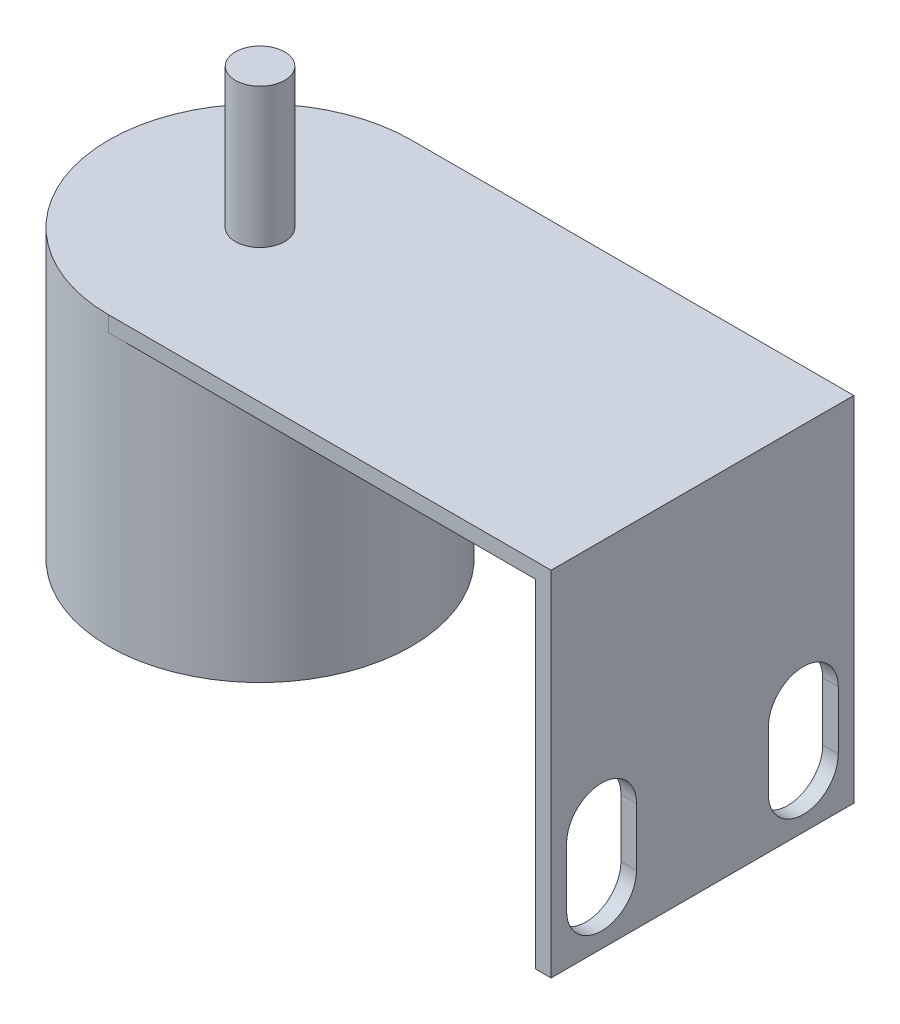
SolidWorks part; units mm, degrees
ref_plane "Plan de face" through (0, 0, 0) normal (0, 0, 1) x (1, 0, 0)
ref_plane "Plan de dessus" through (0, 0, 0) normal (0, 1, 0) x (1, 0, 0)
ref_plane "Plan de droite" through (0, 0, 0) normal (1, 0, 0) x (0, 0, -1)
sketch "Esquisse1" plane through (0, 0, 0) normal (0, 1, 0) x (1, 0, 0)
  circle A0 centre (0, 0) radius 19.5
  dimension "D1" = 39
extrude "Boss.-Extru.1" add sketch "Esquisse1" along normal blind 35
sketch "Esquisse2" plane through (0, 35, 0) normal (0, 1, 0) x (1, 0, 0)
  circle A0 centre (0, 0) radius 3.175
  dimension "D1" = 6.35
extrude "Boss.-Extru.2" add sketch "Esquisse2" along normal blind 20
sketch "Esquisse4" plane through (0, 35, 0) normal (0, 1, 0) x (1, 0, 0)
  line L1 (0, 19.5) -> (57, 19.5)
  line L3 (0, -19.5) -> (57, -19.5)
  line L4 (57, 19.5) -> (57, -19.5)
  circle A0 centre (0, 0) radius 19.5 construction
  arc A1 (0, 19.5) -> (0, -19.5) centre (0, 0) ccw
  point P7 (-19.5, 0)
  dimension "D1" = 76.5
extrude "Boss.-Extru.3" add sketch "Esquisse4" along normal blind 2
sketch "Esquisse5" plane through (0, 35, 0) normal (0, -1, 0) x (1, 0, 0)
  line L0 (57, -19.5) -> (0, -19.5) construction
  line L1 (57, 19.5) -> (55, 19.5)
  line L2 (57, 19.5) -> (57, -19.5)
  line L3 (57, -19.5) -> (55, -19.5)
  line L4 (55, 19.5) -> (55, -19.5)
  dimension "D1" = 2
extrude "Boss.-Extru.4" add sketch "Esquisse5" along normal blind 43.5
sketch "Esquisse6" plane through (57, 0, 0) normal (1, 0, 0) x (0, 0, -1)
  line L0 (-13, 5.5) -> (-13, -2) construction
  line L1 (-8.5, 5.5) -> (-8.5, -2)
  line L2 (-17.5, 5.5) -> (-17.5, -2)
  line L3 (0, 23.3853) -> (0, -17.6361) construction
  line L4 (-19.5, 37) -> (-19.5, -8.5) construction
  line L5 (19.5, -8.5) -> (-19.5, -8.5) construction
  line L6 (13, 5.5) -> (13, -2) construction
  line L7 (8.5, 5.5) -> (8.5, -2)
  line L8 (17.5, 5.5) -> (17.5, -2)
  arc A0 (-8.5, 5.5) -> (-17.5, 5.5) centre (-13, 5.5) ccw
  arc A1 (-17.5, -2) -> (-8.5, -2) centre (-13, -2) ccw
  arc A2 (8.5, 5.5) -> (17.5, 5.5) centre (13, 5.5) cw
  arc A3 (17.5, -2) -> (8.5, -2) centre (13, -2) cw
  point P2 (-13, 1.75)
  point P10 (-13, 10)
  point P11 (-13, -6.5)
  point P12 (-10.9885, -3.4761)
  point P19 (13, 1.75)
  dimension "D1" = 16.5
  dimension "D2" = 9
  dimension "D3" = 2
  dimension "D4" = 2
extrude "Enlèv. mat.-Extru.1" cut sketch "Esquisse6" against normal blind 5
